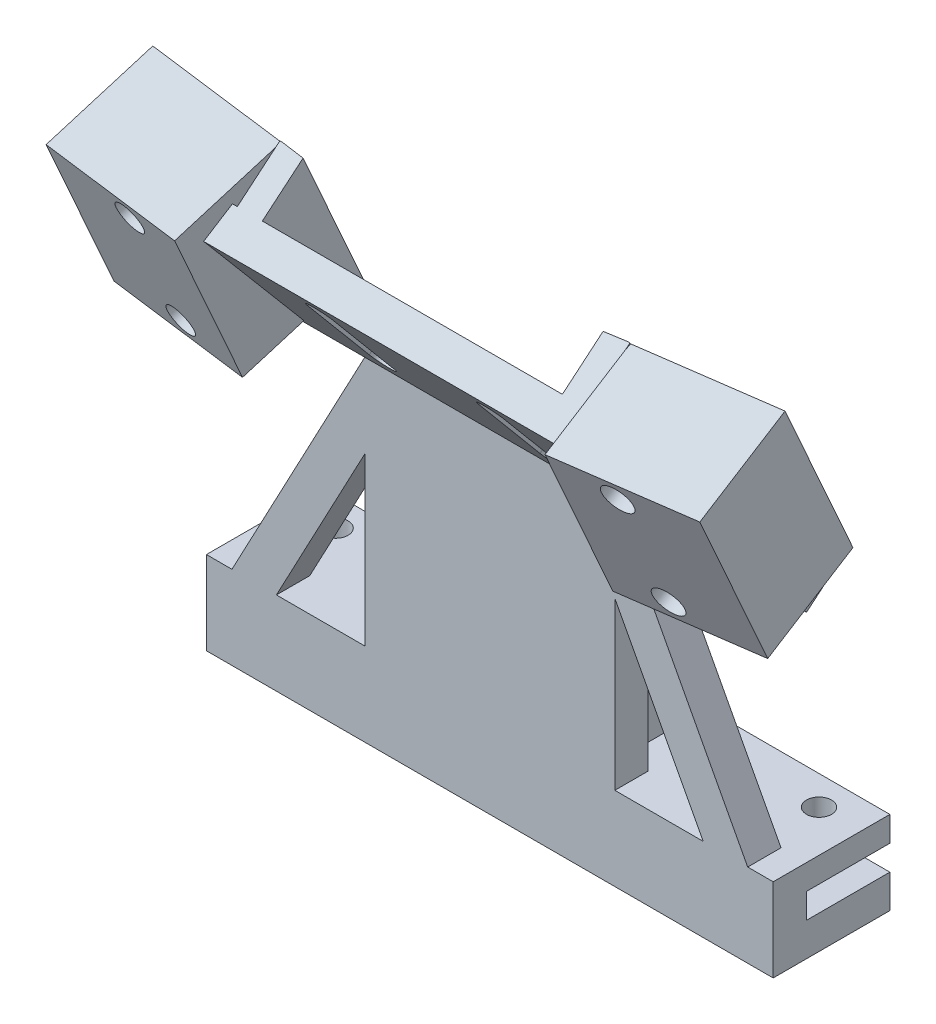
SolidWorks part; units mm, degrees
ref_plane "前视基准面" through (0, 0, 0) normal (0, 0, 1) x (1, 0, 0)
ref_plane "上视基准面" through (0, 0, 0) normal (0, 1, 0) x (1, 0, 0)
ref_plane "右视基准面" through (0, 0, 0) normal (1, 0, 0) x (0, 0, -1)
sketch "草图1" plane through (0, 0, 0) normal (1, 0, 0) x (0, 0, -1)
  line L0 (0, 0) -> (0, 4)
  line L1 (0, 4) -> (-10, 4)
  line L2 (-10, 4) -> (-10, 7)
  line L3 (-10, 7) -> (0, 7)
  line L4 (0, 7) -> (0, 10)
  line L5 (0, 10) -> (-14, 10)
  line L9 (-14, 0) -> (0, 0)
  line L10 (-14, 10) -> (-14, 0)
  dimension "D1" = 3
  dimension "D2" = 4
  dimension "D3" = 3
  dimension "D4" = 10
  dimension "D5" = 4
extrude "凸台-拉伸1" add sketch "草图1" along normal blind 68
sketch "草图2" plane through (0, 10, 0) normal (0, 1, 0) x (1, 0, 0)
  line L0 (34, 0) -> (34, -14) construction
  line L1 (68, 0) -> (0, 0) construction
  line L2 (68, -14) -> (0, -14) construction
  circle A0 centre (5, -3.5) radius 1.5
  circle A1 centre (63, -3.5) radius 1.5
  dimension "D1" = 3
  dimension "D2" = 3.5
  dimension "D3" = 58
extrude "切除-拉伸1" cut sketch "草图2" against normal blind 60
sketch "草图3" plane through (0, 0, 0) normal (0, -1, 0) x (1, 0, 0)
  line L2 (68, 10) -> (0, 10) construction
  line L3 (49, 10) -> (19, 10)
  line L4 (19, 10) -> (19, 14)
  line L5 (19, 14) -> (49, 14)
  line L14 (49, 14) -> (49, 10)
  line L16 (34, 0) -> (34, 18.0549) construction
  line L17 (68, 0) -> (0, 0) construction
  dimension "D1" = 30
extrude "凸台-拉伸2" add sketch "草图3" against normal blind 40
sketch "草图4" plane through (49, 0, 0) normal (1, 0, 0) x (0, 0, -1)
  line L0 (-14, 40) -> (-26.3577, 54.7273)
  line L1 (-26.3577, 54.7273) -> (-23.2935, 57.2985)
  line L2 (-23.2935, 57.2985) -> (-10, 41.4559)
  line L5 (-14, 40) -> (-10, 40)
  line L7 (-10, 40) -> (-10, 41.4559)
  line L8 (-10, 40) -> (-10, 10) construction
  dimension "D1" = 4
  dimension "D2" = 130
extrude "凸台-拉伸3" add sketch "草图4" against normal up to surface (30 mm away) up to face at (19, 25, 12)
sketch "草图5" plane through (0, 9.6334, -11.4806) normal (0, -0.6428, 0.766) x (1, 0, 0)
  line L3 (23.75, 55.3181) -> (23.75, 43.8648) construction
  line L4 (25.25, 55.3181) -> (25.25, 43.8648)
  line L5 (22.25, 55.3181) -> (22.25, 43.8648)
  line L6 (44.25, 55.3181) -> (44.25, 43.8648) construction
  line L7 (42.75, 55.3181) -> (42.75, 43.8648)
  line L8 (45.75, 55.3181) -> (45.75, 43.8648)
  arc A0 (25.25, 55.3181) -> (22.25, 55.3181) centre (23.75, 55.3181) ccw
  arc A1 (22.25, 43.8648) -> (25.25, 43.8648) centre (23.75, 43.8648) ccw
  arc A2 (42.75, 55.3181) -> (45.75, 55.3181) centre (44.25, 55.3181) cw
  arc A3 (45.75, 43.8648) -> (42.75, 43.8648) centre (44.25, 43.8648) cw
  point P8 (23.75, 49.5915)
  point P15 (44.25, 49.5915)
  dimension "D2" = 3
  dimension "D1" = 20.5
extrude "切除-拉伸2" cut sketch "草图5" against normal up to surface (4 mm away) up to face at (34, 49.3772, 16.6468)
sketch "草图6" plane through (19, 0, 0) normal (-1, 0, 0) x (0, 0, 1)
  line L0 (23.2935, 57.2985) -> (26.3577, 54.7273)
  line L1 (26.3577, 54.7273) -> (14, 40)
  line L2 (14, 40) -> (10.9358, 42.5712)
  line L3 (10, 41.4559) -> (23.2935, 57.2985) construction
  line L4 (10.9358, 42.5712) -> (23.2935, 57.2985)
extrude "凸台-拉伸4" add sketch "草图6" along normal blind 23 contours L4 L0 L1 L2
sketch "草图7" plane through (-4, 0, 0) normal (-1, 0, 0) x (0, 0, 1)
  line L0 (23.2935, 57.2985) -> (26.3577, 54.7273)
  line L1 (26.3577, 54.7273) -> (14, 40)
  line L2 (26.3577, 54.7273) -> (14, 40) construction
  line L3 (14, 40) -> (10.9358, 42.5712) construction
  line L4 (14, 40) -> (10.9358, 42.5712)
  line L5 (10.9358, 42.5712) -> (23.2935, 57.2985)
extrude "凸台-拉伸5" add sketch "草图7" against normal blind 23 from surface at -53 contours L5 L0 L1 L4 starting at face at (49, 35.5803, 16.2752)
sketch "草图8" plane through (0, 12.2045, -14.5448) normal (0, 0.6428, -0.766) x (-1, 0, 0)
  line L0 (-72, 39.6408) -> (-52, 39.6408) construction
  line L1 (-72, 39.6408) -> (-49, 39.6408) construction
  line L2 (-52, 39.6408) -> (-52, 58.8659) construction
  line L3 (4, 58.8659) -> (-72, 58.8659) construction
ref_plane "基准面1" through (52, 0, 0) normal (-1, 0, 0) x (0, 0.766, 0.6428)
sketch "草图10" plane through (52, 0, 0) normal (-1, 0, 0) x (0, 0.766, 0.6428)
  line L0 (39.6408, 18.9869) -> (58.8659, 18.9869)
  line L1 (39.6408, 18.9869) -> (39.6408, 20.6535)
  line L2 (58.8659, 18.9869) -> (58.8659, 25.6535)
  line L3 (39.6408, 20.6535) -> (58.8659, 25.6535)
extrude "凸台-拉伸6" add sketch "草图10" against normal blind 3
ref_plane "基准面2" through (72, 0, 0) normal (1, 0, 0) x (0, 0, -1)
sketch "草图11" plane through (72, 0, 0) normal (1, 0, 0) x (0, 0, -1)
  line L0 (-23.2935, 57.2985) -> (-22.2987, 56.1129) construction
  line L2 (-23.2935, 57.2985) -> (-10.9358, 42.5712) construction
  line L3 (-22.2987, 56.1129) -> (-16.6617, 60.8429) construction
  line L4 (-22.2987, 56.1129) -> (-10.2222, 41.7207) construction
  line L5 (-16.6617, 60.8429) -> (-8.4444, 43.2124) construction
  line L8 (-10.2222, 41.7207) -> (-8.4444, 43.2124) construction
ref_plane "基准面3" through (0, 30.3666, 25.4806) normal (0, -0.766, -0.6428) x (-1, 0, 0)
sketch "草图12" plane through (55, 0, 0) normal (1, 0, 0) x (0, 0, -1)
  line L0 (-18.1865, 61.5837) -> (-18.6972, 61.1552) construction
  line L1 (-23.2935, 57.2985) -> (-18.1865, 61.5837) construction
  line L2 (-9.6591, 43.6425) -> (-10.5528, 42.8925) construction
  line L3 (-9.6591, 43.6425) -> (-10.9358, 42.5712) construction
  line L4 (-18.6972, 61.1552) -> (-10.5528, 42.8925) construction
  line L5 (-18.1865, 61.5837) -> (-9.6591, 43.6425) construction
ref_plane "基准面4" through (-0.2247, 0.8985, -2.0148) normal (0.1014, -0.4052, 0.9086) x (0.9949, 0.0413, -0.0926)
sketch "草图15" plane through (-0.2247, 0.8985, -2.0148) normal (0.1014, -0.4052, 0.9086) x (0.9949, 0.0413, -0.0926)
  line L0 (55.5106, 63.4681) -> (55.5106, 62.3539)
  line L1 (55.5106, 43.4717) -> (72.5986, 43.4717)
  line L2 (55.5106, 43.4717) -> (55.5106, 62.3539)
  line L4 (72.5986, 43.4717) -> (72.5986, 62.3539)
  line L5 (72.5986, 62.3539) -> (72.5986, 63.4681)
  line L6 (72.5986, 63.4681) -> (55.5106, 63.4681)
extrude "凸台-拉伸7" add sketch "草图15" against normal blind 0.6667
sketch "草图17" plane through (-0.2247, 0.8985, -2.0148) normal (0.1014, -0.4052, 0.9086) x (0.9949, 0.0413, -0.0926)
  line L1 (55.5106, 63.4681) -> (72.5986, 63.4681)
  line L2 (55.5106, 63.4681) -> (55.5106, 43.4717)
  line L3 (55.5106, 43.4717) -> (72.5986, 43.4717)
  line L4 (72.5986, 63.4681) -> (72.5986, 43.4717)
extrude "凸台-拉伸9" add sketch "草图17" along normal blind 12
sketch "草图19" plane through (-0.2923, 1.1686, -2.6205) normal (-0.1014, 0.4052, -0.9086) x (-0.9949, -0.0413, 0.0926)
  line L0 (-72.5986, 53.4699) -> (-62.5986, 53.4699) construction
  line L1 (-72.5986, 43.4717) -> (-72.5986, 63.4681) construction
  line L2 (-62.5986, 45.9699) -> (-62.5986, 60.9699) construction
  circle A0 centre (-62.5986, 60.9699) radius 1.8
  circle A1 centre (-62.5986, 45.9699) radius 1.8
  point P7 (-62.5986, 53.4699)
extrude "切除-拉伸3" cut sketch "草图19" against normal blind 20
ref_plane "基准面6" through (34, 0, 0) normal (-1, 0, 0) x (0, 0, 1)
sketch "草图20" plane through (34, 0, 0) normal (-1, 0, 0) x (0, 0, 1)
  line L5 (-13.8568, 74.4851) -> (47.7463, 74.4851)
  line L6 (-13.8568, 74.4851) -> (-13.8568, -10.1017)
  line L7 (-13.8568, -10.1017) -> (47.7463, -10.1017)
  line L8 (47.7463, 74.4851) -> (47.7463, -10.1017)
extrude "切除-拉伸4" cut sketch "草图20" along normal blind 65
mirror "镜向7" about plane through (34, 0, 0) normal (-1, 0, 0) of bodies 113
sketch "草图21" plane through (-0.2923, 1.1686, -2.6205) normal (-0.1014, 0.4052, -0.9086) x (-0.9949, -0.0413, 0.0926)
  line L0 (-58.2616, 63.4681) -> (-58.2616, 67.2389) construction
  line L1 (-72.5986, 63.4681) -> (-55.5106, 63.4681) construction
  line L3 (-58.2616, 67.2389) -> (-50.7673, 67.2389)
  line L4 (-58.2616, 67.2389) -> (-58.2616, 40.3658)
  line L5 (-58.2616, 40.3658) -> (-50.7673, 40.3658)
  line L6 (-50.7673, 67.2389) -> (-50.7673, 40.3658)
extrude "切除-拉伸5" cut sketch "草图21" along normal blind 2
sketch "草图22" plane through (0.9908, 3.9612, -8.8824) normal (0.1014, 0.4052, -0.9086) x (-0.9949, 0.0413, -0.0926)
  line L1 (-7.0412, 66.9297) -> (-17.0119, 66.9297)
  line L2 (-7.0412, 66.9297) -> (-7.0412, 41.135)
  line L3 (-7.0412, 41.135) -> (-17.0119, 41.135)
  line L4 (-17.0119, 66.9297) -> (-17.0119, 41.135)
extrude "切除-拉伸6" cut sketch "草图22" along normal blind 2
sketch "草图24" plane through (0, 0, 14) normal (0, 0, 1) x (1, 0, 0)
  line L3 (34, 40) -> (34, -2.8339) construction
  line L4 (49, 40) -> (19, 40) construction
  line L8 (19, 40) -> (3.0592, 10)
  line L12 (0, 10) -> (19, 10) construction
  line L13 (3.0592, 10) -> (8.3952, 10)
  line L15 (8.3952, 10) -> (19, 29.9578)
  line L16 (19, 40) -> (19, 10) construction
  line L17 (19, 40) -> (19, 29.9578)
  line L18 (49, 40) -> (64.9408, 10)
  line L19 (64.9408, 10) -> (59.6048, 10)
  line L20 (59.6048, 10) -> (49, 29.9578)
  line L21 (49, 40) -> (49, 29.9578)
extrude "凸台-拉伸10" add sketch "草图24" against normal blind 4
sketch "草图26" plane through (0, 0, 10) normal (0, 0, -1) x (-1, 0, 0)
  line L0 (-34, 41.4559) -> (-34, 10) construction
  line L1 (-19, 41.4559) -> (-49, 41.4559) construction
  line L2 (-19, 10) -> (-49, 10) construction
sketch "草图28" plane through (0, 10, 0) normal (0, 1, 0) x (1, 0, 0)
  line L0 (34, 0) -> (34, -10) construction
  line L1 (68, 0) -> (0, 0) construction
  line L2 (19, -10) -> (49, -10) construction
sketch "草图29" plane through (34, 0, 0) normal (-1, 0, 0) x (0, 0, 1)
  line L2 (10, 10) -> (2.7924, 10)
  line L5 (10, 41.4559) -> (10, 10)
  line L6 (0, 10) -> (10, 10) construction
  line L8 (2.7924, 10) -> (10, 41.4559)
extrude "凸台-拉伸11" add sketch "草图29" along normal blind 12 and the other way blind 12
